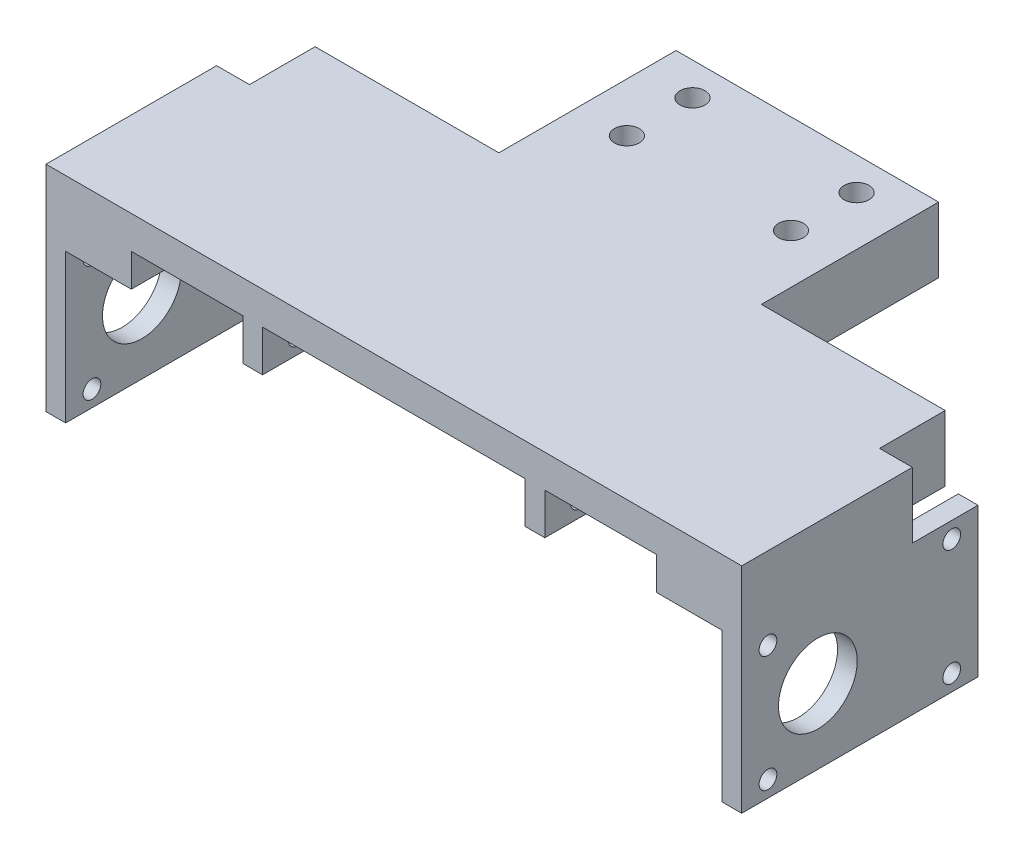
SolidWorks part; units mm, degrees
ref_plane "Front Plane" through (0, 0, 0) normal (0, 0, 1) x (1, 0, 0)
ref_plane "Top Plane" through (0, 0, 0) normal (0, 1, 0) x (1, 0, 0)
ref_plane "Right Plane" through (0, 0, 0) normal (1, 0, 0) x (0, 0, -1)
sketch "Sketch1" plane through (0, 0, 0) normal (0, 1, 0) x (1, 0, 0)
  line L0 (20, 0) -> (20, -27) construction
  line L1 (0, 0) -> (40, 0)
  line L2 (0, 0) -> (0, -27)
  line L3 (0, -27) -> (40, -27)
  line L4 (40, 0) -> (40, -27)
  circle A0 centre (7.5, -5) radius 1.9
  circle A1 centre (7.5, -15) radius 1.9
  circle A2 centre (32.5, -15) radius 1.9
  circle A3 centre (32.5, -5) radius 1.9
  dimension "D3" = 3.8
  dimension "D4" = 25
  dimension "D1" = 40
  dimension "D2" = 27
  dimension "D6" = 5
  dimension "D7" = 10
extrude "Boss-Extrude3" add sketch "Sketch1" along normal blind 10
sketch "Sketch5" plane through (0, 10, 0) normal (0, 1, 0) x (1, 0, 0)
  line L0 (20, 0) -> (20, -27) construction
  line L1 (-30, -27) -> (70, -27)
  line L2 (-30, -27) -> (-30, -63)
  line L3 (-30, -63) -> (70, -63)
  line L4 (70, -27) -> (70, -63)
  line L5 (40, 0) -> (0, 0) construction
  line L6 (0, -27) -> (40, -27) construction
  dimension "D1" = 100
  dimension "D2" = 36
extrude "Boss-Extrude4" add sketch "Sketch5" against normal blind 10
sketch "Sketch6" plane through (70, 0, 0) normal (1, 0, 0) x (0, 0, -1)
  line L0 (-27, 0) -> (-27, 10) construction
  line L1 (-63, 10) -> (-27, 10)
  line L2 (-63, 10) -> (-63, -22.65)
  line L3 (-63, -22.65) -> (-27, -22.65)
  line L4 (-27, 10) -> (-27, -22.65)
  line L5 (-45, 10) -> (-45, -22.65) construction
  line L7 (-63, -11.325) -> (-27, -11.325) construction
  circle A0 centre (-59, -20.175) radius 1.35
  circle A1 centre (-59, -2.475) radius 1.35
  circle A2 centre (-31, -20.175) radius 1.35
  circle A3 centre (-31, -2.475) radius 1.35
  circle A4 centre (-51.4, -11.325) radius 6
  dimension "D2" = 2.7
  dimension "D4" = 17.7
  dimension "D6" = 12
  dimension "D1" = 32.65
  dimension "D3" = 14
  dimension "D5" = 11.325
  dimension "D7" = 7.6
extrude "Boss-Extrude6" add sketch "Sketch6" along normal blind 3
ref_plane "Plane1" through (20, 0, 0) normal (1, 0, 0) x (0, 0, -1)
mirror "Mirror1" about plane through (20, 0, 0) normal (1, 0, 0) of "Boss-Extrude6"
sketch "Sketch7" plane through (0, 0, 63) normal (0, 0, 1) x (1, 0, 0)
  line L1 (-20, 5) -> (60, 5)
  line L2 (-20, 5) -> (-20, -5)
  line L3 (-20, -5) -> (60, -5)
  line L4 (60, 5) -> (60, -5)
  line L5 (-33, 10) -> (73, 10) construction
  line L8 (-30, 0) -> (-30, -22.65) construction
  dimension "D1" = 5
  dimension "D2" = 80
  dimension "D3" = 10
  dimension "D4" = 10
extrude "Cut-Extrude1" cut sketch "Sketch7" against normal blind 36
sketch "Sketch8" plane through (0, 0, 63) normal (0, 0, 1) x (1, 0, 0)
  line L1 (-3, 5) -> (0, 5)
  line L2 (-3, 5) -> (-3, -1.3)
  line L3 (-3, -1.3) -> (0, -1.3)
  line L4 (0, 5) -> (0, -1.3)
  line L5 (60, 5) -> (-20, 5) construction
  line L6 (-30, 0) -> (-20, 0) construction
  line L7 (-30, 0) -> (-30, -22.65) construction
  dimension "D1" = 30
  dimension "D2" = 3
  dimension "D3" = 1.3
extrude "Boss-Extrude7" add sketch "Sketch8" against normal blind 21
mirror "Mirror2" about plane through (20, 0, 0) normal (1, 0, 0) of "Boss-Extrude7"
sketch "Sketch10" plane through (-3, 0, 0) normal (-1, 0, 0) x (0, 0, 1)
  line L0 (63, -1.3) -> (42, -1.3) construction
  line L1 (63, 5) -> (42, 5) construction
  line L2 (51.4, -11.325) -> (51.4, 5) construction
  circle A0 centre (57.7, 1.23) radius 1.35
  circle A1 centre (45.1, 1.23) radius 1.35
  dimension "D1" = 2.7
  dimension "D2" = 2.53
  dimension "D3" = 12.6
extrude "Cut-Extrude3" cut sketch "Sketch10" against normal blind 46
sketch "Sketch11" plane through (-30, 0, 0) normal (1, 0, 0) x (0, 0, -1)
  line L0 (-51.4, -11.325) -> (-27, -11.325) construction
  line L1 (-27, -22.65) -> (-27, 10) construction
  circle A0 centre (-39.95, -11.325) radius 3.75
  circle A1 centre (-51.4, -11.325) radius 6 construction
  dimension "D1" = 11.45
  dimension "D2" = 7.5
extrude "Cut-Extrude4" cut sketch "Sketch11" against normal blind 1.5
mirror "Mirror3" about plane through (20, 0, 0) normal (1, 0, 0) of "Cut-Extrude4"
sketch "Sketch12" plane through (73, 0, 0) normal (1, 0, 0) x (0, 0, -1)
  line L0 (-27, 0) -> (0, 0) construction
  line L1 (-37, 10) -> (-27, 10)
  line L2 (-37, 10) -> (-37, 0)
  line L3 (-37, 0) -> (-27, 0)
  line L4 (-27, 10) -> (-27, 0)
  line L5 (-27, -22.65) -> (-27, 10) construction
  line L6 (-27, 10) -> (-63, 10) construction
  dimension "D1" = 10
extrude "Cut-Extrude5" cut sketch "Sketch12" against normal blind 5
mirror "Mirror4" about plane through (20, 0, 0) normal (1, 0, 0) of "Cut-Extrude5"
equation "\"D2Sketch6\"=2.45"
equation "\"hole\"=2.45"
